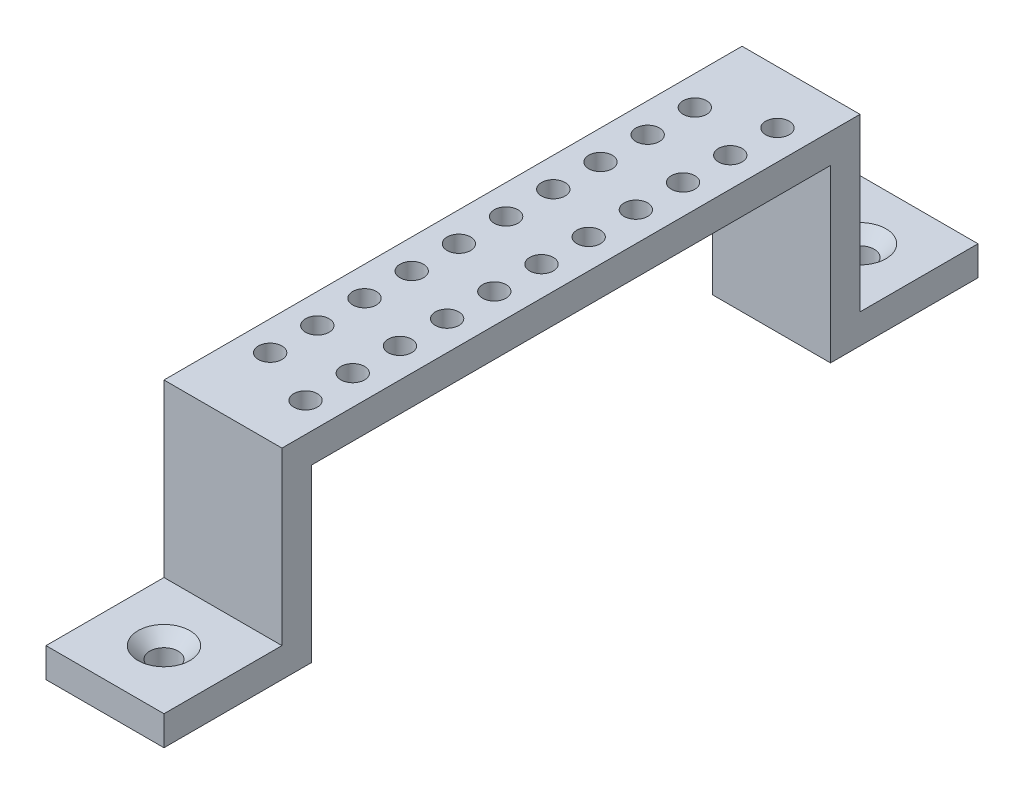
SolidWorks part; units mm, degrees
ref_plane "Front Plane" through (0, 0, 0) normal (0, 0, 1) x (1, 0, 0)
ref_plane "Top Plane" through (0, 0, 0) normal (0, 1, 0) x (1, 0, 0)
ref_plane "Right Plane" through (0, 0, 0) normal (1, 0, 0) x (0, 0, -1)
sketch "Sketch2" plane through (0, 0, 0) normal (0, 1, 0) x (1, 0, 0)
  line L1 (-6.5581, 8.3023) -> (3.4419, 8.3023)
  line L2 (-6.5581, 8.3023) -> (-6.5581, -35.6977)
  line L3 (-6.5581, -35.6977) -> (3.4419, -35.6977)
  line L4 (3.4419, 8.3023) -> (3.4419, -35.6977)
  dimension "D1" = 10
  dimension "D2" = 44
extrude "Boss-Extrude3" add sketch "Sketch2" along normal blind 2.5 contours L2 L3 L4 L1
hole_wizard "Ø2.0mm Dowel Slot3" positions "Sketch16" profile "Sketch15" size "Ø2.0" standard "ANSI Metric" slot yes end condition through all
sketch "Sketch16" plane through (0, 2.5, 0) normal (0, 1, 0) x (1, 0, 0)
  line L0 (-6.5581, 8.3023) -> (-6.5581, -35.6977) construction
  line L1 (-6.5581, 8.3023) -> (3.4419, 8.3023) construction
  line L2 (-4.0581, 8.3023) -> (-4.0581, -35.6977) construction
  line L3 (-6.5581, -35.6977) -> (3.4419, -35.6977) construction
  line L9 (-6.5581, -33.6977) -> (3.4419, -33.6977)
  line L10 (-6.5581, -33.6977) -> (3.4419, -33.6977) construction
  line L11 (-6.5581, -31.6977) -> (3.4419, -31.6977) construction
  line L12 (-6.5581, -29.6977) -> (3.4419, -29.6977) construction
  line L16 (-6.5581, 6.3023) -> (3.4419, 6.3023)
  line L17 (-6.5581, 6.3023) -> (3.4419, 6.3023) construction
  line L18 (-6.5581, 4.3023) -> (3.4419, 4.3023) construction
  line L19 (-6.5581, 2.3023) -> (3.4419, 2.3023) construction
  line L20 (-6.5581, 0.3023) -> (3.4419, 0.3023) construction
  line L21 (-6.5581, -1.6977) -> (3.4419, -1.6977) construction
  line L22 (-6.5581, -3.6977) -> (3.4419, -3.6977) construction
  line L23 (-6.5581, -5.6977) -> (3.4419, -5.6977) construction
  line L24 (-6.5581, -7.6977) -> (3.4419, -7.6977) construction
  line L25 (-6.5581, -23.6977) -> (3.4419, -23.6977) construction
  line L26 (-6.5581, -21.6977) -> (3.4419, -21.6977) construction
  line L27 (-6.5581, -19.6977) -> (3.4419, -19.6977) construction
  line L28 (-6.5581, -17.6977) -> (3.4419, -17.6977) construction
  line L29 (-6.5581, -15.6977) -> (3.4419, -15.6977) construction
  line L30 (-6.5581, -13.6977) -> (3.4419, -13.6977) construction
  line L31 (-6.5581, -11.6977) -> (3.4419, -11.6977) construction
  line L32 (-6.5581, -9.6977) -> (3.4419, -9.6977) construction
  line L33 (-6.5581, -25.6977) -> (3.4419, -25.6977) construction
  line L34 (-6.5581, -27.6977) -> (3.4419, -27.6977) construction
  line L35 (0.9419, 8.3023) -> (0.9419, -35.6977) construction
  line L37 (3.4419, 8.3023) -> (3.4419, -35.6977) construction
  point P0 (-4.0581, 4.3023)
  point P96 (-4.0581, 0.3023)
  point P98 (-4.0581, -3.6977)
  point P100 (-4.0581, -7.6977)
  point P102 (-4.0581, -11.6977)
  point P104 (-4.0581, -15.6977)
  point P106 (-4.0581, -19.6977)
  point P108 (-4.0581, -23.6977)
  point P110 (-4.0581, -27.6977)
  point P112 (-4.0581, -31.6977)
  point P121 (0.9419, 2.3023)
  point P123 (0.9419, -1.6977)
  point P125 (0.9419, -5.6977)
  point P127 (0.9419, -9.6977)
  point P129 (0.9419, -13.6977)
  point P131 (0.9419, -17.6977)
  point P133 (0.9419, -21.6977)
  point P135 (0.9419, -25.6977)
  point P137 (0.9419, -29.6977)
  point P139 (0.9419, -33.6977)
  point P146 (0.9419, 6.3023)
  dimension "D1" = 2.5
  dimension "D2" = 4
  dimension "D5" = 2.5
  dimension "D3" = 2
  dimension "D4" = 2
sketch "Sketch15" plane through (-4.0581, 2.5, -4.3023) normal (1, 0, 0) x (0, 0, 1)
  line L0 (0, 0) -> (0, 2.5)
  line L1 (0, 2.5) -> (1, 2.5)
  line L2 (1, 2.5) -> (1, 0)
  line L5 (1, 0) -> (0, 0)
  line L11 (0, -6.35) -> (0, 107.95) construction
  dimension "Thru Hole Dia." = 2
  dimension "Thru Hole Depth" = 2.5
sketch "Sketch18" plane through (0, 0, 35.6977) normal (0, 0, 1) x (1, 0, 0)
  line L1 (-6.5581, 2.5) -> (3.4419, 2.5)
  line L2 (-6.5581, 2.5) -> (-6.5581, 0)
  line L3 (-6.5581, 0) -> (3.4419, 0)
  line L4 (3.4419, 2.5) -> (3.4419, 0)
extrude "Boss-Extrude4" add sketch "Sketch18" along normal blind 2.5
sketch "Sketch19" plane through (0, 0, -8.3023) normal (0, 0, -1) x (-1, 0, 0)
  line L1 (-3.4419, 0) -> (6.5581, 0)
  line L2 (-3.4419, 0) -> (-3.4419, 2.5)
  line L3 (-3.4419, 2.5) -> (6.5581, 2.5)
  line L4 (6.5581, 0) -> (6.5581, 2.5)
extrude "Boss-Extrude5" add sketch "Sketch19" along normal blind 2.5
sketch "Sketch20" plane through (0, 0, 0) normal (0, -1, 0) x (1, 0, 0)
  line L2 (-6.5581, 35.6977) -> (3.4419, 35.6977)
  line L3 (-6.5581, 35.6977) -> (3.4419, 35.6977) construction
  line L5 (3.4419, -8.3023) -> (-6.5581, -8.3023)
  line L6 (3.4419, -8.3023) -> (-6.5581, -8.3023) construction
  line L7 (3.4419, 38.1977) -> (-6.5581, 38.1977)
  line L8 (3.4419, 38.1977) -> (3.4419, 35.6977)
  line L9 (3.4419, 35.6977) -> (-6.5581, 35.6977)
  line L10 (-6.5581, 38.1977) -> (-6.5581, 35.6977)
  line L11 (3.4419, -8.3023) -> (-6.5581, -8.3023)
  line L12 (3.4419, -8.3023) -> (3.4419, -10.8023)
  line L13 (3.4419, -10.8023) -> (-6.5581, -10.8023)
  line L14 (-6.5581, -8.3023) -> (-6.5581, -10.8023)
  dimension "D1" = 2.5
  dimension "D2" = 2.5
extrude "Boss-Extrude6" add sketch "Sketch20" along normal blind 14.5
sketch "Sketch22" plane through (0, 0, -10.8023) normal (0, 0, -1) x (-1, 0, 0)
  line L2 (6.5581, -12) -> (-3.4419, -12)
  line L3 (6.5581, -12) -> (-3.4419, -12) construction
  line L4 (-3.4419, -14.5) -> (6.5581, -14.5)
  line L5 (-3.4419, -14.5) -> (-3.4419, -12)
  line L6 (-3.4419, -12) -> (6.5581, -12)
  line L7 (6.5581, -14.5) -> (6.5581, -12)
  dimension "D1" = 2.5
extrude "Boss-Extrude7" add sketch "Sketch22" along normal blind 10
sketch "Sketch23" plane through (0, 0, 38.1977) normal (0, 0, 1) x (1, 0, 0)
  line L0 (3.4419, -14.5) -> (3.4419, 2.5) construction
  line L1 (-6.5581, -14.5) -> (3.4419, -14.5)
  line L2 (-6.5581, -14.5) -> (-6.5581, -12)
  line L3 (-6.5581, -12) -> (3.4419, -12)
  line L4 (3.4419, -14.5) -> (3.4419, -12)
  dimension "D1" = 2.5
extrude "Boss-Extrude8" add sketch "Sketch23" along normal blind 10
hole_wizard "CSK for M2 Flat Head Machine Screw1" positions "Sketch26" profile "Sketch27" countersink size "M2" standard "ANSI Metric" end condition through all
sketch "Sketch26" plane through (0, -12, 0) normal (0, 1, 0) x (1, 0, 0)
  line L0 (-6.5581, 20.8023) -> (-6.5581, 10.8023) construction
  line L1 (-6.5581, 20.8023) -> (3.4419, 20.8023) construction
  point P0 (-1.5581, 15.8023)
  dimension "D1" = 5
  dimension "D2" = 5
sketch "Sketch27" plane through (-1.5581, -12, -15.8023) normal (1, 0, 0) x (0, 0, 1)
  line L0 (0, 0) -> (0, 2.5)
  line L1 (0, 2.5) -> (1.2, 2.5)
  line L2 (1.2, 2.5) -> (1.2, 1)
  line L3 (1.2, 1) -> (2.2, 0)
  line L5 (2.2, 0) -> (0, 0)
  line L6 (-1.2, 1) -> (-2.2, 0) construction
  line L11 (0, -6.35) -> (0, 107.95) construction
  dimension "Thru Hole Dia." = 2.4
  dimension "Thru Hole Depth" = 2.5
  dimension "Near C'Sink Dia." = 4.4
  dimension "Near C'Sink Angle" = 90
hole_wizard "CSK for M2 Flat Head Machine Screw2" positions "Sketch28" profile "Sketch29" countersink size "M2" standard "ANSI Metric" end condition through all
sketch "Sketch28" plane through (0, -12, 0) normal (0, 1, 0) x (1, 0, 0)
  line L0 (3.4419, -48.1977) -> (-6.5581, -48.1977) construction
  line L1 (3.4419, -48.1977) -> (3.4419, -38.1977) construction
  point P0 (-1.5581, -43.1977)
  dimension "D1" = 5
  dimension "D2" = 5
sketch "Sketch29" plane through (-1.5581, -12, 43.1977) normal (1, 0, 0) x (0, 0, 1)
  line L0 (0, 0) -> (0, 2.5)
  line L1 (0, 2.5) -> (1.2, 2.5)
  line L2 (1.2, 2.5) -> (1.2, 1)
  line L3 (1.2, 1) -> (2.2, 0)
  line L5 (2.2, 0) -> (0, 0)
  line L6 (-1.2, 1) -> (-2.2, 0) construction
  line L11 (0, -6.35) -> (0, 107.95) construction
  dimension "Thru Hole Dia." = 2.4
  dimension "Thru Hole Depth" = 2.5
  dimension "Near C'Sink Dia." = 4.4
  dimension "Near C'Sink Angle" = 90
